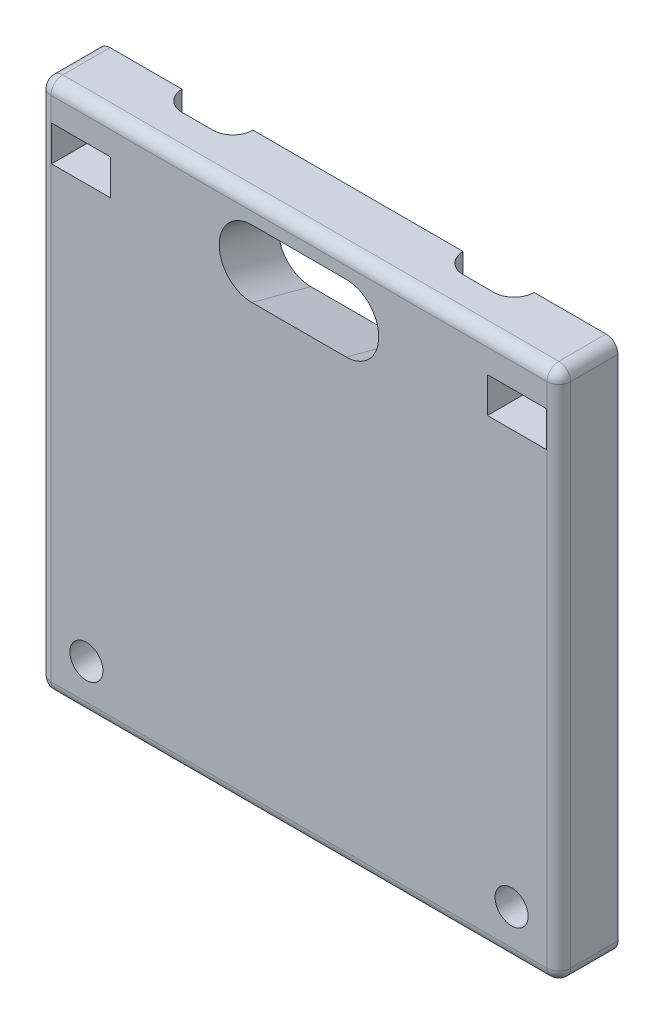
SolidWorks part; units mm, degrees
ref_plane "Front Plane" through (0, 0, 0) normal (0, 0, 1) x (1, 0, 0)
ref_plane "Top Plane" through (0, 0, 0) normal (0, 1, 0) x (1, 0, 0)
ref_plane "Right Plane" through (0, 0, 0) normal (1, 0, 0) x (0, 0, -1)
sketch "Sketch1" plane through (0, 0, 0) normal (0, 0, 1) x (1, 0, 0)
  line L1 (-22, 22.5) -> (22, 22.5)
  line L2 (-22, 22.5) -> (-22, -22.5)
  line L3 (-22, -22.5) -> (22, -22.5)
  line L4 (22, 22.5) -> (22, -22.5)
  line L5 (-22, 22.5) -> (22, -22.5) construction
  line L6 (-22, -22.5) -> (22, 22.5) construction
  point P0 (0, 0)
  dimension "D1" = 44
  dimension "D2" = 45
extrude "Base" add sketch "Sketch1" along normal blind 5
sketch "Sketch2" plane through (0, 22.5, 0) normal (0, 1, 0) x (1, 0, 0)
  line L0 (22, 0) -> (-22, 0) construction
  line L1 (-14.9, 0) -> (-8.9, 0)
  line L2 (0, 0) -> (0, -5) construction
  line L3 (22, -5) -> (-22, -5) construction
  line L5 (-14.9, 0) -> (-14.9, -5) construction
  line L6 (-13.2, -1.7) -> (-10.6, -1.7)
  line L7 (13.2, -1.7) -> (10.6, -1.7)
  line L8 (14.9, 0) -> (8.9, 0)
  arc A2 (-14.9, 0) -> (-13.2, -1.7) centre (-13.2, 0) ccw
  arc A3 (-10.6, -1.7) -> (-8.9, 0) centre (-10.6, 0) ccw
  arc A4 (14.9, 0) -> (13.2, -1.7) centre (13.2, 0) cw
  arc A5 (10.6, -1.7) -> (8.9, 0) centre (10.6, 0) cw
  point P0 (-11.9, 0)
  dimension "D1" = 6
  dimension "D2" = 11.9
  dimension "D3" = 1.7
extrude "Wire Grooves" cut sketch "Sketch2" against normal through all
sketch "Sketch4" plane through (0, 0, 0) normal (0, 0, -1) x (-1, 0, 0)
  line L0 (0, 22.5) -> (0, -22.5) construction
  line L3 (-22, 16.5291) -> (22, 16.5291) construction
  line L4 (-22, -22.5) -> (-22, 22.5) construction
  line L5 (22, 22.5) -> (22, -22.5) construction
  line L6 (-8.9, 22.5) -> (8.9, 22.5) construction
  line L8 (8.9, -22.5) -> (-8.9, -22.5) construction
  dimension "D1" = 5.9709
ref_plane "Screw Insertion Hole Reference" through (0, 1.1072, 4.1323) normal (0, -0.2588, -0.9659) x (-1, 0, 0)
sketch "Sketch3" plane through (0, 0.5961, 4.2692) normal (0, -0.2588, -0.9659) x (-1, 0, 0)
  line L0 (0, 0.5291) -> (0, 22.2625) construction
  line L1 (-4, 16.2925) -> (4, 16.2925) construction
  line L2 (-8.9, 22.2625) -> (8.9, 22.2625) construction
  line L3 (-4, 19.0425) -> (4, 19.0425)
  line L4 (-4, 13.5425) -> (4, 13.5425)
  arc A1 (-4, 19.0425) -> (-4, 13.5425) centre (-4, 16.2925) ccw
  arc A2 (4, 13.5425) -> (4, 19.0425) centre (4, 16.2925) ccw
  point P5 (0, 16.2925)
  point P12 (0, 0)
  dimension "D1" = 5.97
  dimension "D2" = 2.75
  dimension "D3" = 8
extrude "Screw Insertion Hole" cut sketch "Sketch3" against normal through all both and the other way through all
sketch "Sketch5" plane through (0, 0, 0) normal (0, 0, -1) x (-1, 0, 0)
  line L0 (-18.45, 22.5) -> (-18.45, -22.5) construction
  line L1 (-22, 22.5) -> (-14.9, 22.5) construction
  line L2 (-14.9, -22.5) -> (-22, -22.5) construction
  line L3 (0, 22.5) -> (0, -22.5) construction
  line L7 (-20.95, 19.5) -> (-15.95, 19.5)
  line L8 (-20.95, 19.5) -> (-20.95, 16.5)
  line L9 (-20.95, 16.5) -> (-15.95, 16.5)
  line L10 (-15.95, 19.5) -> (-15.95, 16.5)
  line L11 (-20.95, 19.5) -> (-15.95, 16.5) construction
  line L12 (-20.95, 16.5) -> (-15.95, 19.5) construction
  line L16 (-8.9, 22.5) -> (8.9, 22.5) construction
  line L17 (8.9, -22.5) -> (-8.9, -22.5) construction
  line L18 (20.95, 16.5) -> (15.95, 16.5)
  line L19 (15.95, 19.5) -> (15.95, 16.5)
  line L20 (20.95, 19.5) -> (15.95, 19.5)
  line L21 (20.95, 19.5) -> (20.95, 16.5)
  point P12 (-18.45, 18)
  dimension "D1" = 5
  dimension "D2" = 3
  dimension "D3" = 3
extrude "Zip Tie Slots" cut sketch "Sketch5" against normal through all
sketch "Sketch6" plane through (0, 0, 0) normal (0, 0, -1) x (-1, 0, 0)
  line L1 (-22, -22.5) -> (-22, 22.5) construction
  line L2 (-14.9, -22.5) -> (-22, -22.5) construction
  line L4 (0, 22.5) -> (0, -22.5) construction
  line L6 (-8.9, 22.5) -> (8.9, 22.5) construction
  line L7 (8.9, -22.5) -> (-8.9, -22.5) construction
  circle A0 centre (-18, -18.5) radius 1.4
  circle A2 centre (18, -18.5) radius 1.4
  dimension "D1" = 2.8
  dimension "D2" = 4
  dimension "D3" = 4
extrude "Mount Clamping Holes" cut sketch "Sketch6" against normal through all
fillet "Edge Fillets" radius 1 8 edges at (-22, 0, 5) (22, 0, 5) (0, -22.5, 5) (0, 22.5, 5) (22, 22.5, 2.5) (22, -22.5, 2.5) (-22, -22.5, 2.5) (-22, 22.5, 2.5)
